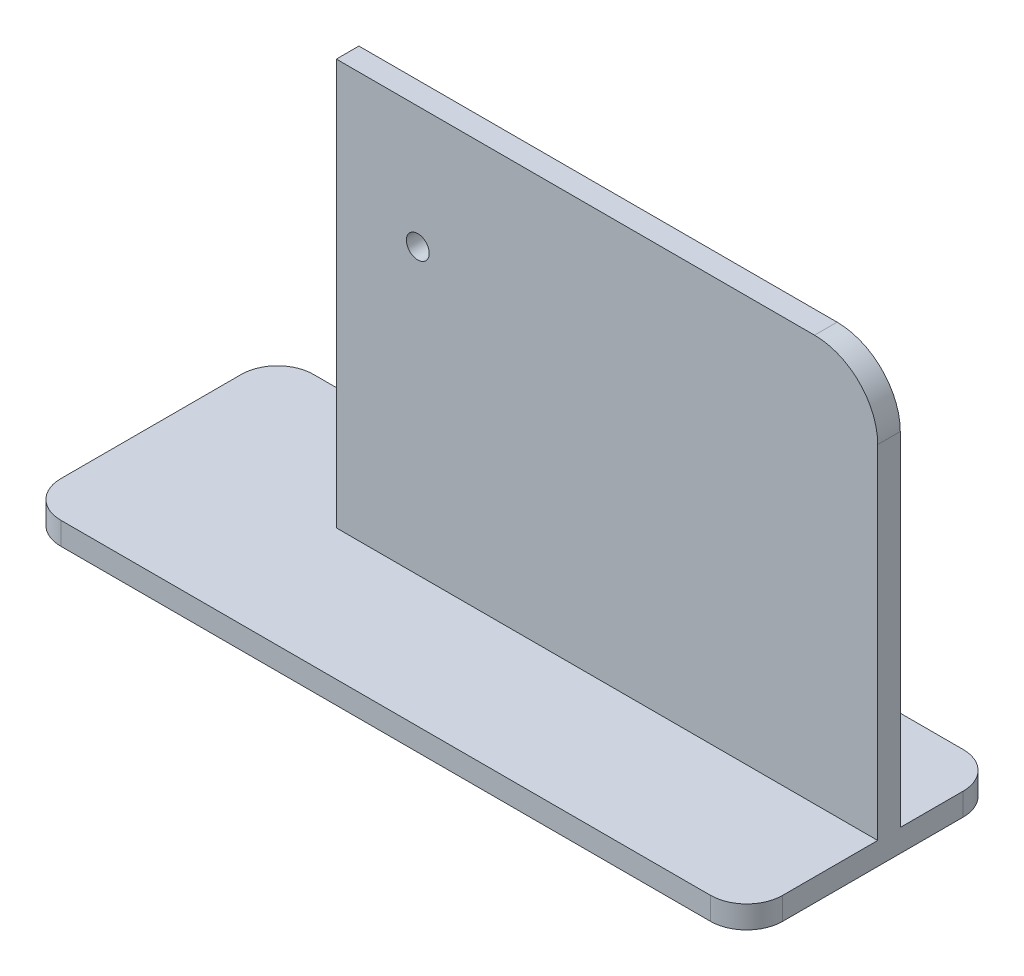
SolidWorks part; units mm, degrees
ref_plane "Alzado" through (0, 0, 0) normal (0, 0, 1) x (1, 0, 0)
ref_plane "Planta" through (0, 0, 0) normal (0, 1, 0) x (1, 0, 0)
ref_plane "Vista lateral" through (0, 0, 0) normal (1, 0, 0) x (0, 0, -1)
sketch "Croquis4" plane through (0, 0, 0) normal (0, 0, 1) x (1, 0, 0)
  line L0 (30.4069, -15.1368) -> (30.4069, 22.8632)
  line L1 (23.4069, 29.8632) -> (-29.5931, 29.8632)
  line L2 (-29.5931, 29.8632) -> (-29.5931, -15.1368)
  line L3 (-29.5931, -15.1368) -> (30.4069, -15.1368)
  line L4 (-29.5931, 29.8632) -> (-20.5643, 29.8632) construction
  line L5 (-20.5643, 29.8632) -> (-20.5643, 16.3632) construction
  arc A0 (30.4069, 22.8632) -> (23.4069, 29.8632) centre (23.4069, 22.8632) ccw
  circle A1 centre (-20.5643, 16.3632) radius 1.2679
  dimension "D1" = 7
extrude "Saliente-Extruir3" add sketch "Croquis4" along normal blind 2.5
sketch "Croquis5" plane through (0, -15.1368, 0) normal (0, -1, 0) x (1, 0, 0)
  line L0 (30.4069, 13.0315) -> (30.4069, -6.9685)
  line L1 (26.4069, -10.9685) -> (-45.5931, -10.9685)
  line L2 (-49.5931, -6.9685) -> (-49.5931, 13.0315)
  line L3 (-45.5931, 17.0315) -> (26.4069, 17.0315)
  arc A0 (26.4069, 17.0315) -> (30.4069, 13.0315) centre (26.4069, 13.0315) cw
  arc A1 (30.4069, -6.9685) -> (26.4069, -10.9685) centre (26.4069, -6.9685) cw
  arc A2 (-45.5931, -10.9685) -> (-49.5931, -6.9685) centre (-45.5931, -6.9685) cw
  arc A3 (-49.5931, 13.0315) -> (-45.5931, 17.0315) centre (-45.5931, 13.0315) cw
  dimension "D1" = 4
extrude "Saliente-Extruir4" add sketch "Croquis5" along normal blind 2.5
